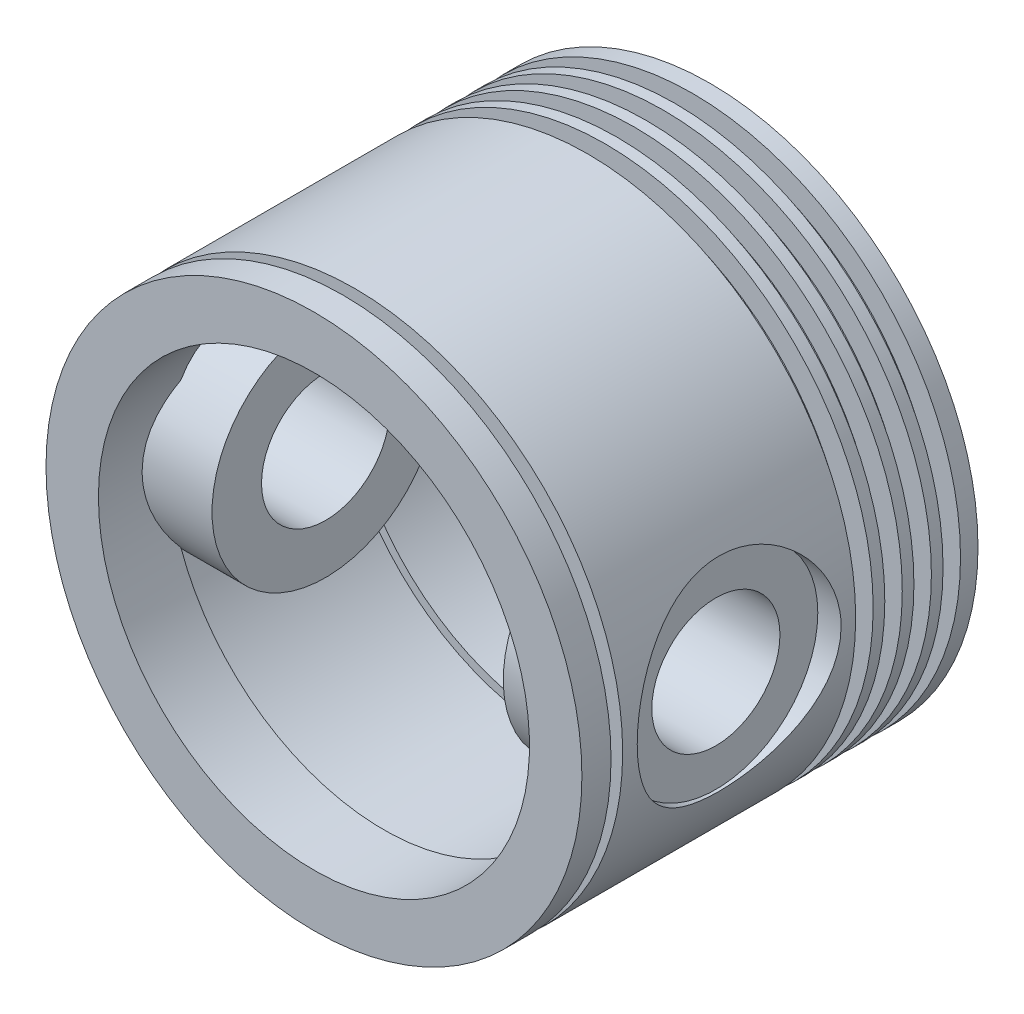
SolidWorks part; units mm, degrees
ref_plane "Front Plane" through (0, 0, 0) normal (0, 0, 1) x (1, 0, 0)
ref_plane "Top Plane" through (0, 0, 0) normal (0, 1, 0) x (1, 0, 0)
ref_plane "Right Plane" through (0, 0, 0) normal (1, 0, 0) x (0, 0, -1)
sketch "Sketch1" plane through (0, 0, 0) normal (0, 1, 0) x (1, 0, 0)
  line L0 (0, 90.7287) -> (0, -101.5327) construction
  line L1 (-178.5109, 0) -> (184.404, 0) construction
  line L2 (0, 62) -> (37, 62)
  line L3 (37, 62) -> (37, 0)
  line L4 (46, 0) -> (46, 68)
  line L5 (0, 62) -> (0, 73.6833)
  line L6 (37, 0) -> (46, 0)
  arc A0 (46, 68) -> (0, 73.6833) centre (0, -115.3167) ccw
  dimension "D5" = 189
  dimension "D1" = 62
  dimension "D2" = 68
  dimension "D3" = 37
  dimension "D4" = 46
revolve "Revolve1" add sketch "Sketch1" angle 360 about L0
sketch "Sketch2" plane through (0, 0, 0) normal (0, 1, 0) x (1, 0, 0)
  line L0 (0, 0) -> (0, 62) construction
  line L1 (-37, 62) -> (37, 62) construction
  line L2 (0, 27) -> (37, 27) construction
  line L3 (37, 0) -> (37, 62) construction
  line L4 (-37, 0) -> (37, 0) construction
  line L5 (37, 42) -> (37, 12)
  line L6 (37, 42) -> (38.5, 42)
  line L7 (38.5, 42) -> (38.5, 12)
  line L8 (38.5, 12) -> (37, 12)
  point P13 (37, 27)
  dimension "D1" = 27
  dimension "D2" = 30
  dimension "D3" = 38.5
revolve "Cut-Revolve1" cut sketch "Sketch2" angle 360 about L0
sketch "Sketch4" plane through (0, 0, 0) normal (1, 0, 0) x (0, 0, -1)
  line L0 (12, 0) -> (42, 0) construction
  line L1 (12, -38.5) -> (12, 38.5) construction
  line L2 (42, 38.5) -> (42, -38.5) construction
  circle A0 centre (27, 0) radius 19.5
  dimension "D1" = 39
extrude "Boss-Extrude1" add sketch "Sketch4" along normal up to surface (13.5 mm away) from offset 25 up to face at (38.5, 0, -42)
mirror "Mirror1" about plane through (0, 0, 0) normal (1, 0, 0) of "Boss-Extrude1"
sketch "Sketch5" plane through (0, 0, 0) normal (1, 0, 0) x (0, 0, -1)
  circle A0 centre (27, 0) radius 11
  dimension "D1" = 22
extrude "Cut-Extrude1" cut sketch "Sketch5" against normal mid plane 121
sketch "Sketch6" plane through (-25, 0, 0) normal (1, 0, 0) x (0, 0, -1)
  circle A0 centre (27, 0) radius 17.5
  dimension "D1" = 35
extrude "Cut-Extrude4" cut sketch "Sketch6" against normal up to surface (4 mm away) from offset 17 offset against normal yes
mirror "Mirror2" about plane through (0, 0, 0) normal (1, 0, 0) of "Cut-Extrude4"
sketch "Sketch8" plane through (0, 0, 0) normal (0, 1, 0) x (1, 0, 0)
  line L0 (0, 0) -> (0, 68) construction
  line L1 (-46, 68) -> (46, 68) construction
  line L2 (46, 65) -> (42, 65)
  line L3 (46, 44.5) -> (46, 68) construction
  line L4 (42, 65) -> (42, 62)
  line L5 (42, 62) -> (46, 62)
  line L6 (46, 62) -> (46, 65)
  dimension "D1" = 3
  dimension "D2" = 3
  dimension "D3" = 42
revolve "Cut-Revolve2" cut sketch "Sketch8" angle 360 about L0
pattern_linear "LPattern1" count 4 spacing 5 along (0, 0, 1) of "Cut-Revolve2"
sketch "Sketch9" plane through (0, 0, 0) normal (0, 1, 0) x (1, 0, 0)
  line L0 (-46, 7) -> (-42, 7)
  line L1 (-42, 7) -> (-42, 5)
  line L2 (-42, 5) -> (-46, 5)
  line L3 (-46, 9.5) -> (-46, 0) construction
  line L5 (-46, 0) -> (46, 0) construction
  line L6 (-46, 5) -> (-46, 7)
  line L7 (0, 0) -> (0, 73.4702) construction
  dimension "D1" = 7
  dimension "D2" = 2
  dimension "D3" = 42
revolve "Cut-Revolve3" cut sketch "Sketch9" angle 360 about L7
